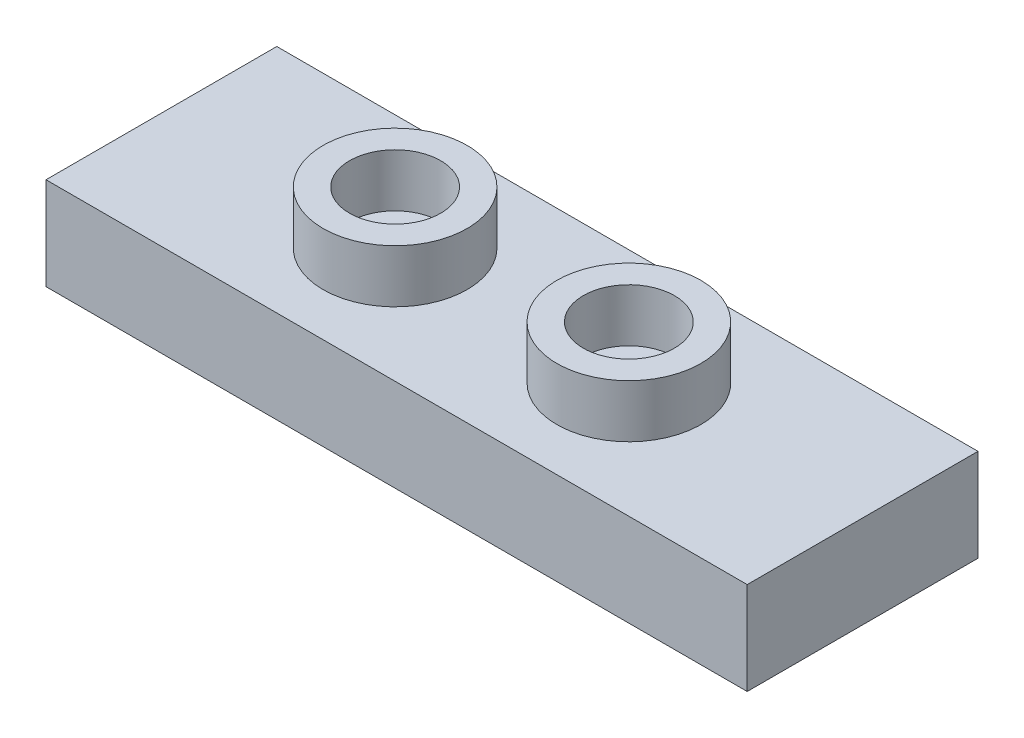
SolidWorks part; units mm, degrees
ref_plane "Front Plane" through (0, 0, 0) normal (0, 0, 1) x (1, 0, 0)
ref_plane "Top Plane" through (0, 0, 0) normal (0, 1, 0) x (1, 0, 0)
ref_plane "Right Plane" through (0, 0, 0) normal (1, 0, 0) x (0, 0, -1)
sketch "Sketch1" plane through (0, 0, 0) normal (0, 1, 0) x (1, 0, 0)
  line L1 (-11.925, 3.925) -> (11.925, 3.925)
  line L2 (-11.925, 3.925) -> (-11.925, -3.925)
  line L3 (-11.925, -3.925) -> (11.925, -3.925)
  line L4 (11.925, 3.925) -> (11.925, -3.925)
  line L5 (-11.925, 3.925) -> (11.925, -3.925) construction
  line L6 (-11.925, -3.925) -> (11.925, 3.925) construction
  point P0 (0, 0)
  dimension "D1" = 23.85
  dimension "D2" = 7.85
extrude "Boss-Extrude1" add sketch "Sketch1" against normal blind 3.15
shell "Shell1" thickness 1.5
sketch "Sketch2" plane through (0, 0, 0) normal (0, 1, 0) x (1, 0, 0)
  line L1 (-11.925, 3.925) -> (-11.925, -3.925) construction
  line L2 (-11.925, -3.925) -> (11.925, -3.925) construction
  line L3 (0, 6.171) -> (0, -7.4865) construction
  circle A0 centre (-3.975, 0) radius 2.45
  circle A1 centre (-3.975, 0) radius 1.55
  circle A2 centre (3.975, 0) radius 1.55
  circle A3 centre (3.975, 0) radius 2.45
  dimension "D2" = 4.9
  dimension "D4" = 3.1
  dimension "D1" = 7.95
  dimension "D3" = 3.925
extrude "Boss-Extrude2" add sketch "Sketch2" along normal blind 1.8
